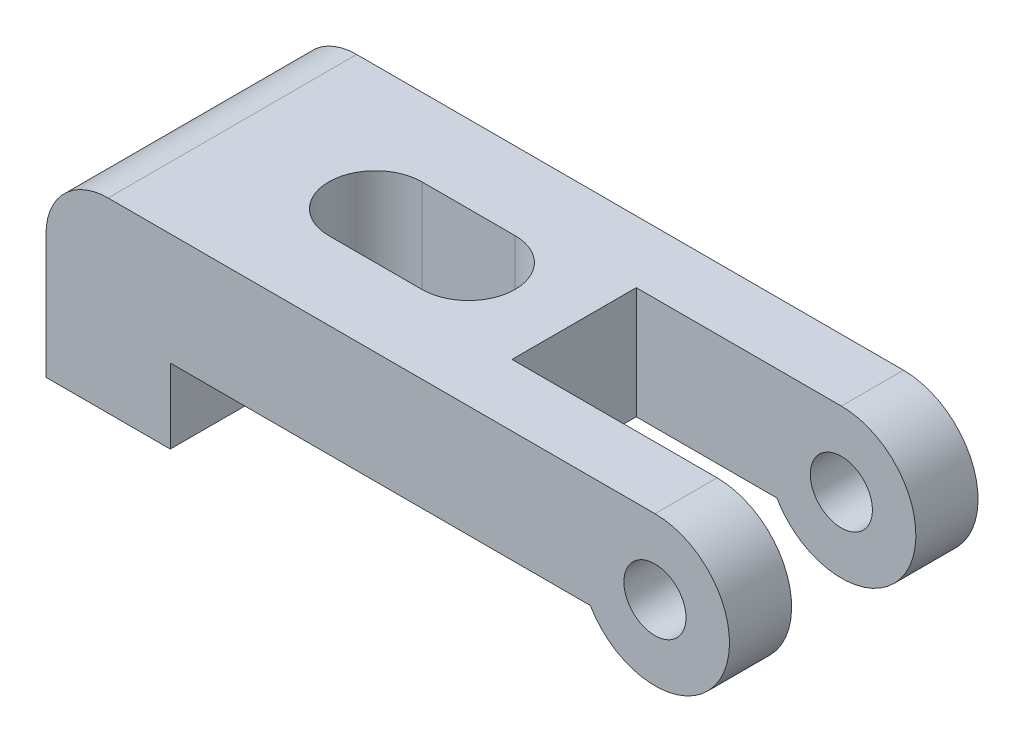
SolidWorks part; units mm, degrees
ref_plane "Plan de face" through (0, 0, 0) normal (0, 0, 1) x (1, 0, 0)
ref_plane "Plan de dessus" through (0, 0, 0) normal (0, 1, 0) x (1, 0, 0)
ref_plane "Plan de droite" through (0, 0, 0) normal (1, 0, 0) x (0, 0, -1)
sketch "Esquisse1" plane through (0, 0, 0) normal (0, 0, 1) x (1, 0, 0)
  line L0 (0, 0) -> (0, 200)
  line L1 (100, 300) -> (980, 300)
  line L2 (0, 0) -> (200, 0)
  line L3 (200, 0) -> (200, 120)
  line L4 (200, 120) -> (876.077, 120)
  line L5 (980, 393.3343) -> (980, 22.4484) construction
  line L6 (1178.0812, 180) -> (766.2027, 180) construction
  arc A0 (100, 300) -> (0, 200) centre (100, 200) ccw
  arc A1 (876.077, 120) -> (980, 300) centre (980, 180) ccw
  circle A2 centre (980, 180) radius 50
  point P9 (0, 300)
  point P14 (980, 180)
  point P17 (1100, 180)
  point P18 (876.077, 120)
  dimension "D5" = 100
  dimension "D1" = 240
  dimension "D8" = 100
  dimension "D2" = 300
  dimension "D3" = 120
  dimension "D4" = 200
  dimension "D6" = 980
  dimension "D7" = 120
extrude "Boss.-Extru.1" add sketch "Esquisse1" along normal blind 400
sketch "Esquisse2" plane through (0, 300, 0) normal (0, 1, 0) x (1, 0, 0)
  line L0 (-124.9053, -200) -> (1204.9862, -200) construction
  line L2 (330, -200) -> (480, -200) construction
  line L3 (330, -125) -> (480, -125)
  line L4 (330, -275) -> (480, -275)
  line L5 (0, -400) -> (0, 0) construction
  line L6 (980, -400) -> (100, -400) construction
  line L7 (980, 0) -> (100, 0) construction
  line L8 (650, -300) -> (1250, -300)
  line L9 (650, -300) -> (650, -100)
  line L10 (650, -100) -> (1250, -100)
  line L11 (1250, -300) -> (1250, -100)
  line L12 (1100, -400) -> (1100, 0) construction
  arc A0 (330, -125) -> (330, -275) centre (330, -200) ccw
  arc A1 (480, -275) -> (480, -125) centre (480, -200) ccw
  point P6 (405, -200)
  dimension "D5" = 100
  dimension "D1" = 125
  dimension "D2" = 150
  dimension "D3" = 330
  dimension "D4" = 150
  dimension "D6" = 450
  dimension "D7" = 600
  dimension "D8" = 200
extrude "Enlèv. mat.-Extru.1" cut sketch "Esquisse2" against normal through all
